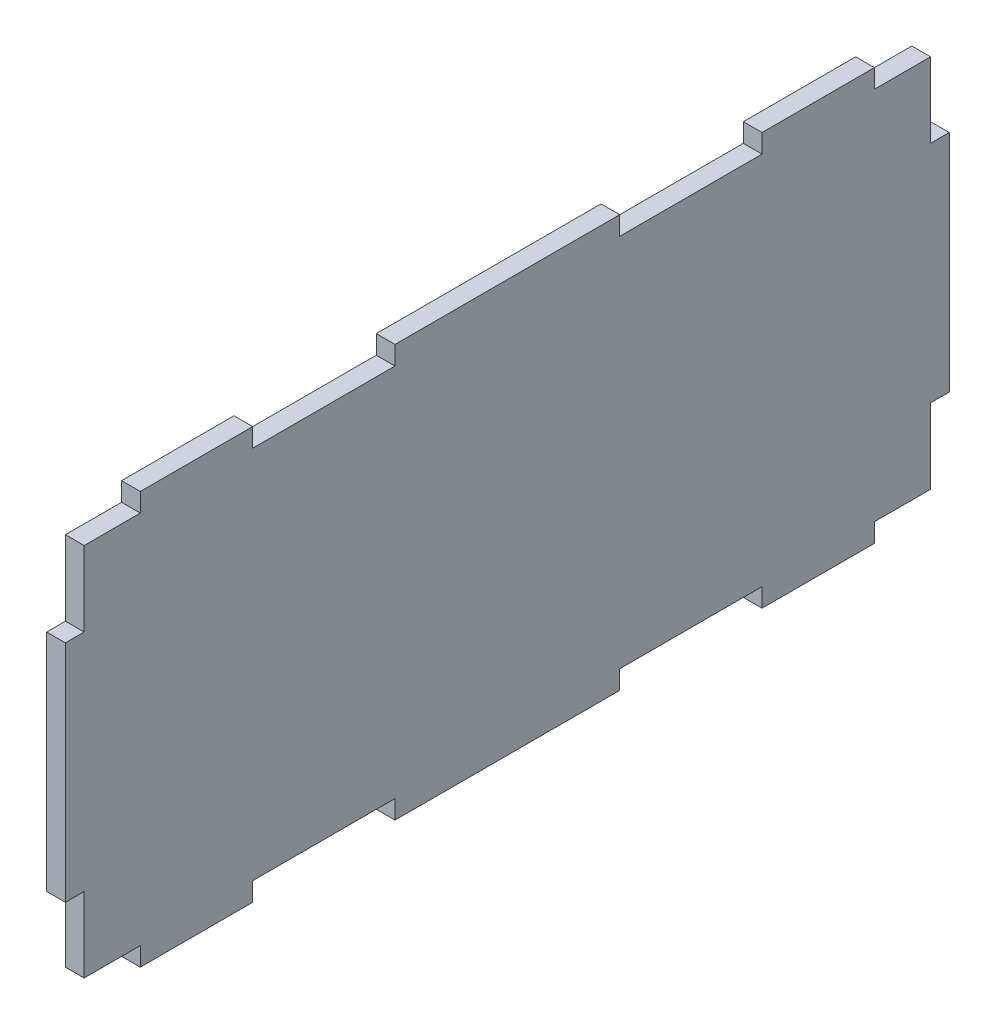
SolidWorks part; units mm, degrees
ref_plane "Front Plane" through (0, 0, 0) normal (0, 0, 1) x (1, 0, 0)
ref_plane "Top Plane" through (0, 0, 0) normal (0, 1, 0) x (1, 0, 0)
ref_plane "Right Plane" through (0, 0, 0) normal (1, 0, 0) x (0, 0, -1)
sketch "Sketch1" plane through (0, 0, 0) normal (1, 0, 0) x (0, 0, -1)
  line L0 (-113, 0) -> (113, 0) construction
  line L1 (113, -50) -> (-113, -50)
  line L2 (113, -50) -> (113, 50)
  line L3 (113, 50) -> (-113, 50)
  line L4 (-113, -50) -> (-113, 50)
  line L5 (113, -50) -> (-113, 50) construction
  line L6 (113, 50) -> (-113, -50) construction
  line L7 (0, -50) -> (0, 50) construction
  line L8 (113, -30) -> (118, -30)
  line L9 (98, 50) -> (68, 50)
  line L10 (98, 50) -> (98, 55)
  line L11 (98, 55) -> (68, 55)
  line L12 (68, 50) -> (68, 55)
  line L13 (0, 50) -> (30, 50)
  line L14 (0, 50) -> (0, 55)
  line L15 (-30, 55) -> (30, 55)
  line L16 (30, 50) -> (30, 55)
  line L17 (113, 0) -> (118, 0)
  line L18 (113, 0) -> (113, 30)
  line L19 (113, 30) -> (118, 30)
  line L20 (118, -30) -> (118, 30)
  line L21 (98, -50) -> (98, -55)
  line L22 (68, -50) -> (68, -55)
  line L23 (98, -55) -> (68, -55)
  line L24 (30, -50) -> (30, -55)
  line L25 (-30, -55) -> (30, -55)
  line L26 (-30, -50) -> (-30, -55)
  line L27 (-68, -50) -> (-68, -55)
  line L28 (-98, -50) -> (-98, -55)
  line L29 (-98, -55) -> (-68, -55)
  line L30 (-113, -30) -> (-118, -30)
  line L31 (-118, -30) -> (-118, 30)
  line L32 (-113, 30) -> (-118, 30)
  line L33 (-98, 50) -> (-98, 55)
  line L34 (-68, 50) -> (-68, 55)
  line L35 (-98, 55) -> (-68, 55)
  line L36 (-30, 50) -> (-30, 55)
  line L37 (30, 50) -> (-30, 50)
  line L38 (-68, 50) -> (-98, 50)
  line L39 (-113, 30) -> (-113, -30)
  line L40 (-98, -50) -> (-68, -50)
  line L41 (-30, -50) -> (30, -50)
  line L42 (68, -50) -> (98, -50)
  line L43 (113, -30) -> (113, 30)
  line L44 (98, 50) -> (68, 50)
  point P0 (0, 0)
  point P17 (98, 52.5)
  point P32 (0, -55)
  dimension "D1" = 226
  dimension "D2" = 100
  dimension "D3" = 5
  dimension "D4" = 5
  dimension "D5" = 15
  dimension "D6" = 30
  dimension "D7" = 30
  dimension "D8" = 5
  dimension "D9" = 30
extrude "Boss-Extrude1" add sketch "Sketch1" along normal blind 5 contours L4 L1 L2 L3 | L35 L33 L3 L34 | L28 L29 L27 L1 | L4 L32 L31 L30 | L12 L3 L10 L11 | L37 L36 L15 L16 | L25 L24 L41 L26 | L23 L22 L42 L21 | L43 L8 L20 L19
